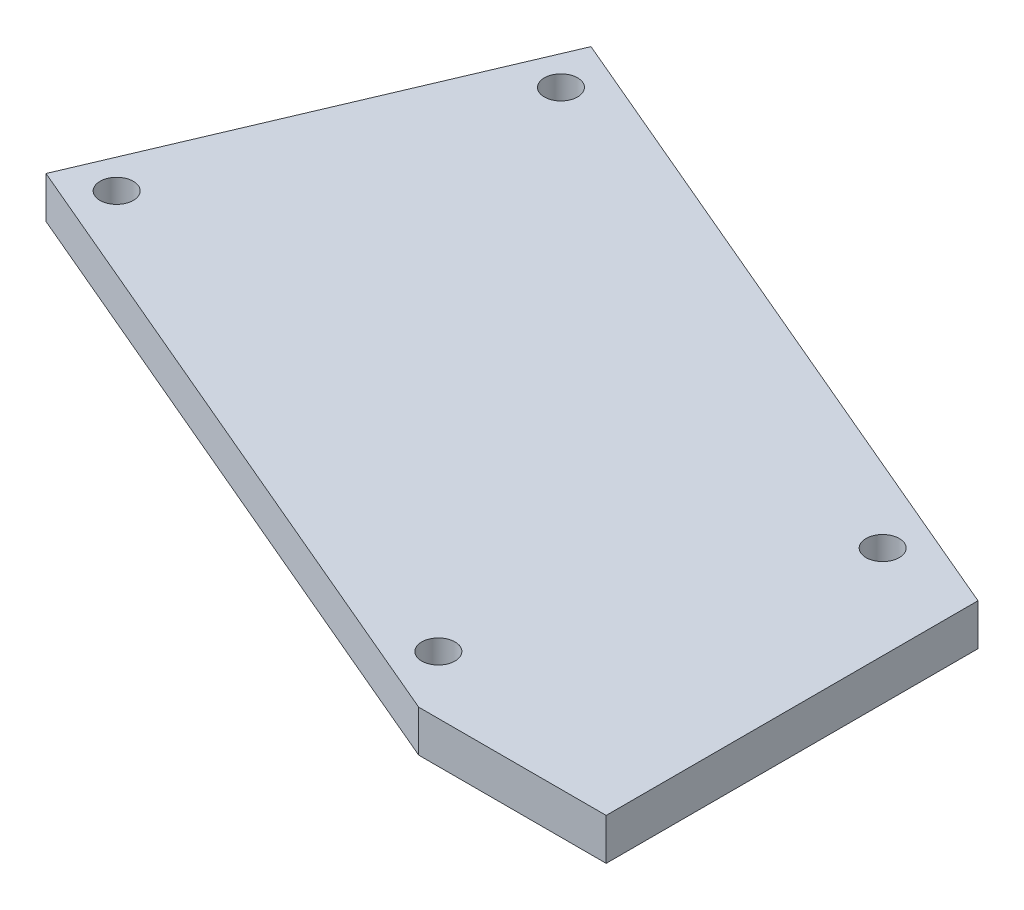
SolidWorks part; units mm, degrees
material "Birch Ply"
ref_plane "Front Plane" through (0, 0, 0) normal (0, 0, 1) x (1, 0, 0)
ref_plane "Top Plane" through (0, 0, 0) normal (0, 1, 0) x (1, 0, 0)
ref_plane "Right Plane" through (0, 0, 0) normal (1, 0, 0) x (0, 0, -1)
sketch "Sketch1" plane through (0, 0, 0) normal (0, 1, 0) x (1, 0, 0)
  line L0 (0, 0) -> (0, 43.9365) construction
  line L1 (0, 0) -> (-51.4509, 21.8816)
  line L2 (-51.4509, 21.8816) -> (-63.8768, -7.3358)
  line L3 (-63.8768, -7.3358) -> (-14.324, -28.4102)
  line L4 (-17.2577, -23.9745) -> (-4.2485, 6.6146) construction
  line L5 (0, 0) -> (0, -28.4102)
  line L6 (0, -28.4102) -> (-14.324, -28.4102)
  circle A0 centre (-49.8994, 18.0338) radius 1.27
  circle A1 centre (-60.029, -5.7843) radius 1.27
  circle A2 centre (-17.2577, -23.9745) radius 1.27
  circle A3 centre (-7.1281, -0.1565) radius 1.27
  dimension "D5" = 2.54
  dimension "D6" = 2.54
  dimension "D7" = 2.54
  dimension "D8" = 2.54
  dimension "D1" = 66.96
  dimension "D2" = 53.848
  dimension "D3" = 31.75
  dimension "D4" = 14.324
  dimension "D9" = 2.9337
  dimension "D10" = 2.9337
  dimension "D11" = 2.9337
  dimension "D12" = 2.9337
  dimension "D13" = 2.9337
  dimension "D14" = 2.9337
  dimension "D15" = 2.9337
extrude "Boss-Extrude1" add sketch "Sketch1" along normal blind 3.175
